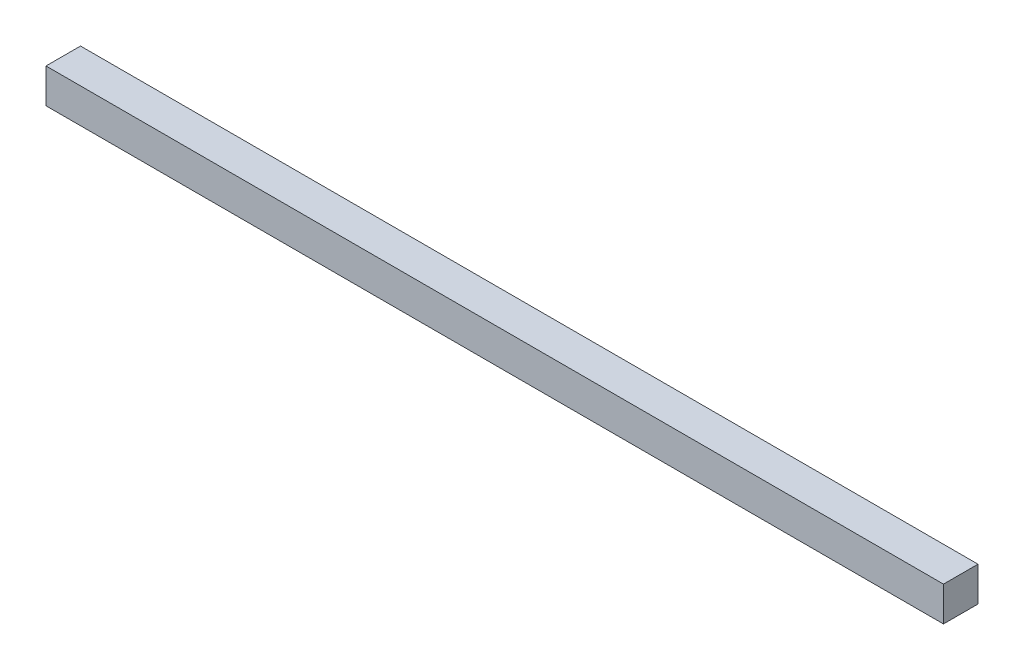
SolidWorks part; units mm, degrees
ref_plane "Front Plane" through (0, 0, 0) normal (0, 0, 1) x (1, 0, 0)
ref_plane "Top Plane" through (0, 0, 0) normal (0, 1, 0) x (1, 0, 0)
ref_plane "Right Plane" through (0, 0, 0) normal (1, 0, 0) x (0, 0, -1)
sketch "Sketch1" plane through (0, 0, 0) normal (0, 1, 0) x (1, 0, 0)
  line L1 (0, 0) -> (990.6, 0)
  line L2 (0, 0) -> (0, 38.1)
  line L3 (0, 38.1) -> (990.6, 38.1)
  line L4 (990.6, 0) -> (990.6, 38.1)
  dimension "D1" = 990.6
  dimension "D2" = 38.1
extrude "Extrude1" add sketch "Sketch1" along normal blind 38.1
